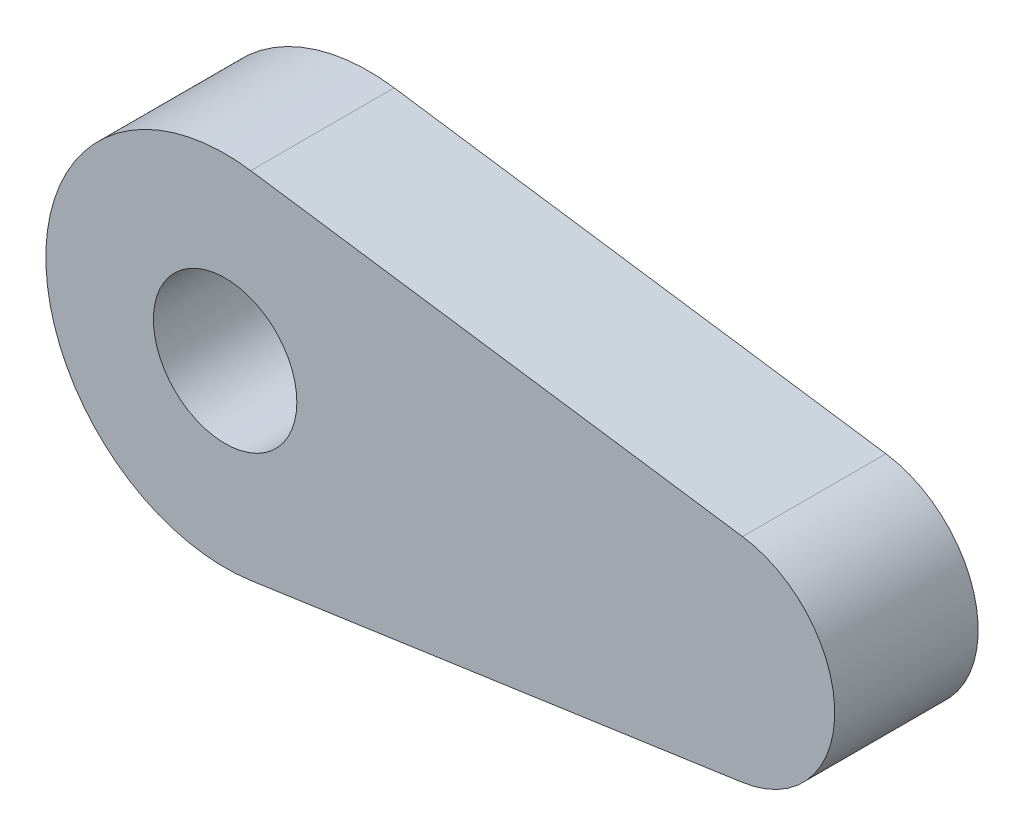
SolidWorks part; units mm, degrees
ref_plane "前视基准面" through (0, 0, 0) normal (0, 0, 1) x (1, 0, 0)
ref_plane "上视基准面" through (0, 0, 0) normal (0, 1, 0) x (1, 0, 0)
ref_plane "右视基准面" through (0, 0, 0) normal (1, 0, 0) x (0, 0, -1)
sketch "草图1" plane through (0, 0, 0) normal (0, 0, 1) x (1, 0, 0)
  line L0 (-21.5198, 3.4595) -> (-14.6627, 2.4698)
  line L1 (-21.5198, -1.4892) -> (-14.6627, -0.4994)
  arc A0 (-21.5198, 3.4595) -> (-21.5198, -1.4892) centre (-21.877, 0.9852) ccw
  arc A1 (-14.6627, -0.4994) -> (-14.6627, 2.4698) centre (-14.877, 0.9852) ccw
  circle A2 centre (-21.877, 0.9852) radius 1
  point P9 (0, 0)
  dimension "D1" = 5
  dimension "D2" = 3
  dimension "D4" = 2
  dimension "D3" = 7
extrude "凸台-拉伸1" add sketch "草图1" along normal blind 2
